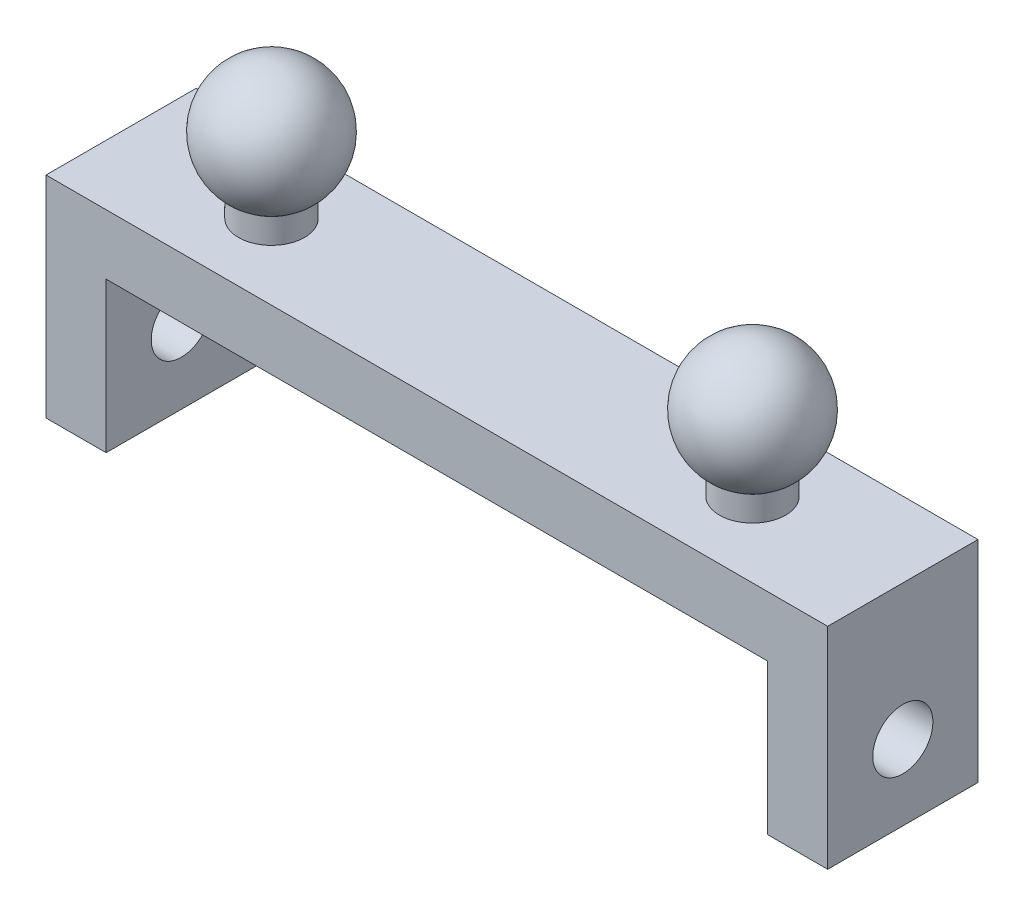
SolidWorks part; units mm, degrees
ref_plane "前视基准面" through (0, 0, 0) normal (0, 0, 1) x (1, 0, 0)
ref_plane "上视基准面" through (0, 0, 0) normal (0, 1, 0) x (1, 0, 0)
ref_plane "右视基准面" through (0, 0, 0) normal (1, 0, 0) x (0, 0, -1)
other "Configuration Table"
sketch "草图1" plane through (0, 0, 0) normal (0, 0, 1) x (1, 0, 0)
  line L0 (0, 0) -> (13, 0)
  line L1 (13, 0) -> (13, -7)
  line L2 (13, -7) -> (11, -7)
  line L3 (11, -7) -> (11, -2)
  line L4 (11, -2) -> (0, -2)
  line L5 (0, -2) -> (0, 0)
  dimension "D1" = 7
  dimension "D2" = 2
  dimension "D3" = 2
  dimension "D4" = 13
extrude "凸台-拉伸1" add sketch "草图1" along normal mid plane 5
mirror "镜向1" about plane through (0, 0, 0) normal (1, 0, 0) of "凸台-拉伸1"
sketch "草图2" plane through (13, 0, 0) normal (1, 0, 0) x (0, 0, -1)
  line L0 (-2.5, -7) -> (2.5, -7) construction
  circle A0 centre (0, -4.5) radius 1
  dimension "D1" = 2
  dimension "D2" = 2.5
extrude "切除-拉伸1" cut sketch "草图2" against normal through all
ref_plane "基准面1" through (8, 0, 0) normal (1, 0, 0) x (0, 0, -1)
sketch "草图3" plane through (8, 0, 0) normal (1, 0, 0) x (0, 0, -1)
  line L0 (0, 0) -> (0, 4.5)
  line L1 (1.1, 0.8297) -> (1.1, 0)
  line L2 (-2.5, 0) -> (2.5, 0) construction
  line L3 (1.1, 0) -> (0, 0)
  arc A0 (1.1, 0.8297) -> (0, 4.5) centre (0, 2.5) ccw
  dimension "D1" = 2
  dimension "D3" = 2.5
  dimension "D2" = 1.1
revolve "旋转1" add sketch "草图3" angle 360 about L0
ref_plane "基准面2" through (-8, 0, 0) normal (-1, 0, 0) x (0, 0, 1)
sketch "草图4" plane through (-8, 0, 0) normal (-1, 0, 0) x (0, 0, 1)
  line L0 (0, 0) -> (0, 4.5)
  line L1 (1.1, 0.8297) -> (1.1, 0)
  line L2 (2.5, 0) -> (-2.5, 0) construction
  line L3 (1.1, 0) -> (0, 0)
  arc A1 (1.1, 0.8297) -> (0, 4.5) centre (0, 2.5) ccw
  dimension "D1" = 4
  dimension "D3" = 2.5
  dimension "D2" = 1.1
revolve "旋转2" add sketch "草图4" angle 360 about L0
